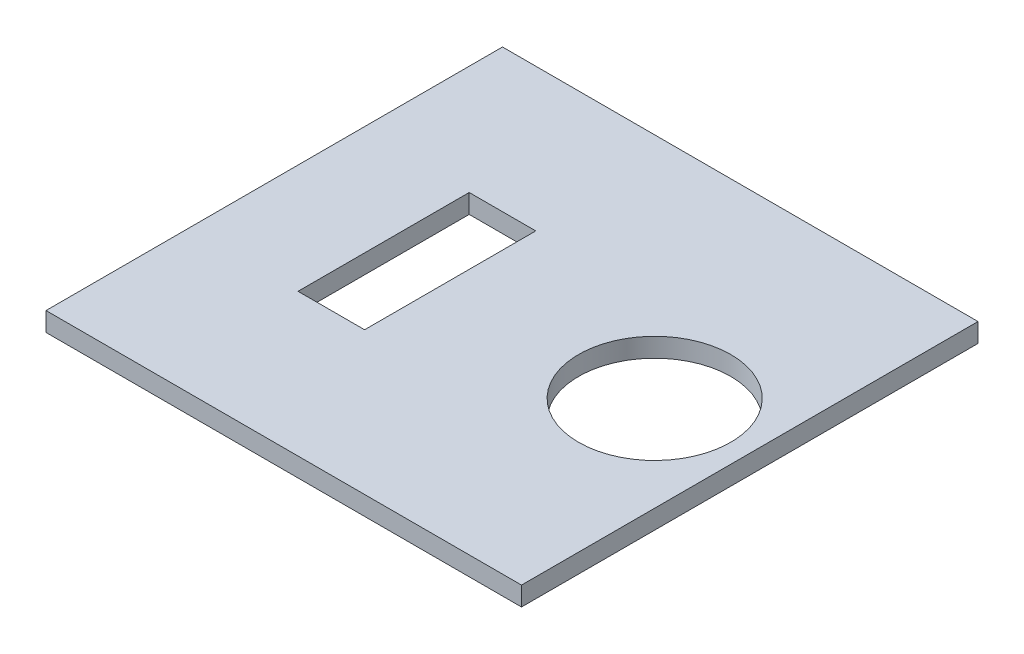
SolidWorks part; units mm, degrees
ref_plane "Front Plane" through (0, 0, 0) normal (0, 0, 1) x (1, 0, 0)
ref_plane "Top Plane" through (0, 0, 0) normal (0, 1, 0) x (1, 0, 0)
ref_plane "Right Plane" through (0, 0, 0) normal (1, 0, 0) x (0, 0, -1)
sketch "Sketch1" plane through (0, 0, 0) normal (0, 1, 0) x (1, 0, 0)
  line L1 (-12.5, -12) -> (12.5, -12)
  line L2 (-12.5, -12) -> (-12.5, 12)
  line L3 (-12.5, 12) -> (12.5, 12)
  line L4 (12.5, -12) -> (12.5, 12)
  line L5 (-12.5, -12) -> (12.5, 12) construction
  line L6 (-12.5, 12) -> (12.5, -12) construction
  line L7 (-6.75, -4.5) -> (-3.25, -4.5)
  line L8 (-6.75, -4.5) -> (-6.75, 4.5)
  line L9 (-6.75, 4.5) -> (-3.25, 4.5)
  line L10 (-3.25, -4.5) -> (-3.25, 4.5)
  line L11 (-6.75, -4.5) -> (-3.25, 4.5) construction
  line L12 (-6.75, 4.5) -> (-3.25, -4.5) construction
  circle A0 centre (7.5, 0) radius 4
  point P0 (0, 0)
  point P6 (-5, 0)
  dimension "D3" = 8
  dimension "D1" = 25
  dimension "D2" = 24
  dimension "D4" = 9
  dimension "D5" = 3.5
  dimension "D6" = 12
  dimension "D7" = 12
  dimension "D8" = 7.5
  dimension "D9" = 12.5
extrude "Boss-Extrude1" add sketch "Sketch1" along normal blind 1
